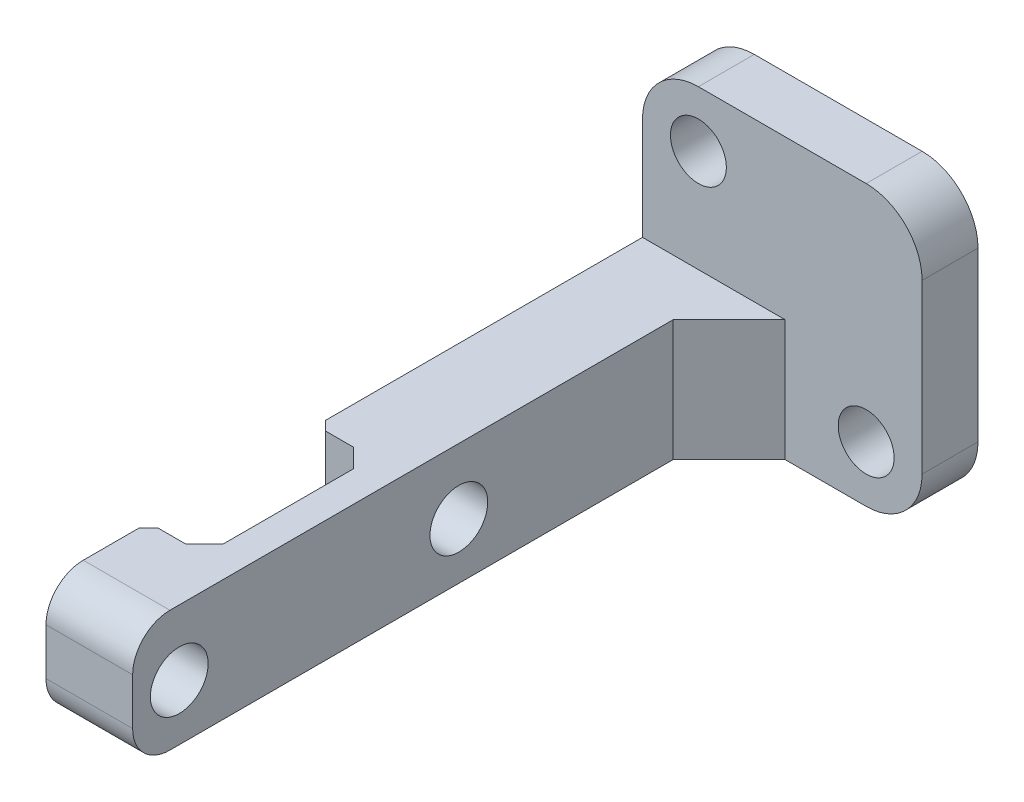
SolidWorks part; units mm, degrees
ref_plane "Front Plane" through (0, 0, 0) normal (0, 0, 1) x (1, 0, 0)
ref_plane "Top Plane" through (0, 0, 0) normal (0, 1, 0) x (1, 0, 0)
ref_plane "Right Plane" through (0, 0, 0) normal (1, 0, 0) x (0, 0, -1)
sketch "Sketch1" plane through (0, 0, 0) normal (0, 1, 0) x (1, 0, 0)
  line L1 (0, 0) -> (28, 0)
  line L2 (0, 0) -> (0, 5)
  line L3 (0, 5) -> (28, 5)
  line L4 (28, 0) -> (28, 5)
  dimension "D1" = 5
  dimension "D2" = 28
extrude "Boss-Extrude1" add sketch "Sketch1" along normal blind 20
chamfer "Chamfer1" distance 15 angle 45 1 edges at (28, 0, -2.5)
sketch "Sketch2" plane through (0, 0, 0) normal (0, 0, 1) x (1, 0, 0)
  line L0 (5, 18) -> (5, 2) construction
  line L1 (5, 18) -> (5, 2)
  line L2 (0, 0) -> (13, 0) construction
  line L3 (5, 6.5) -> (9.6488, 6.5)
  line L4 (5, 6.5) -> (5, 0)
  line L5 (5, 0) -> (9.6488, 0)
  line L6 (9.6488, 6.5) -> (9.6488, 0)
  line M5 (0, 0) -> (13, 0)
  dimension "D1" = 6.5
extrude "Boss-Extrude2" add sketch "Sketch2" along normal blind 28 contours L6 L3 L1 L4 M5
sketch "Sketch3" plane through (0, 0, 0) normal (0, -1, 0) x (1, 0, 0)
  line L0 (5, 28) -> (5, 0) construction
  line L1 (5, 22.5) -> (8, 22.5)
  line L2 (5, 22.5) -> (5, 13.5)
  line L3 (5, 13.5) -> (8, 13.5)
  line L4 (8, 22.5) -> (8, 13.5)
  dimension "D1" = 3
  dimension "D2" = 1
  dimension "D3" = 1
extrude "Cut-Extrude1" cut sketch "Sketch3" against normal blind 12.8
chamfer "Chamfer2" distance 1 angle 45 2 edges at (8, 3.25, 13.5) (8, 3.25, 22.5)
fillet "Fillet1" radius 2 2 edges at (7.3244, 6.5, 28) (7.3244, 0, 28)
chamfer "Chamfer3" distance 0.5 angle 45 2 edges at (5, 3.25, 22.5) (5, 3.25, 13.5)
sketch "Sketch4" plane through (5, 0, 0) normal (-1, 0, 0) x (0, 0, 1)
  arc A0 (25.5, 1.45) -> (25.5, 4.55) centre (25.5, 3) ccw construction
  arc A1 (25.5, 4.55) -> (25.5, 1.45) centre (25.5, 3) ccw construction
  arc A2 (10.5, 4.55) -> (10.5, 1.45) centre (10.5, 3) ccw construction
  arc A3 (10.5, 1.45) -> (10.5, 4.55) centre (10.5, 3) ccw construction
  arc A4 (25.5, 1.45) -> (25.5, 4.55) centre (25.5, 3) ccw
  arc A5 (25.5, 4.55) -> (25.5, 1.45) centre (25.5, 3) ccw
  arc A6 (10.5, 4.55) -> (10.5, 1.45) centre (10.5, 3) ccw
  arc A7 (10.5, 1.45) -> (10.5, 4.55) centre (10.5, 3) ccw
extrude "Cut-Extrude2" cut sketch "Sketch4" against normal blind 12.8
chamfer "Chamfer4" distance 3 angle 45 2 edges at (5, 3.25, 0) (9.6488, 3.25, 0)
chamfer "Chamfer5" distance 3 angle 45 1 edges at (7.3244, 6.5, 0)
sketch "Sketch8" plane through (0, 20, 0) normal (0, 1, 0) x (1, 0, 0)
  line L0 (22.254, 1.284) -> (22.254, 1.158) construction
  line L1 (22.254, 0.746) -> (22.254, 1.158) construction
  line L2 (22.254, 3.714) -> (22.254, 1.284) construction
  line L3 (22.254, 3.714) -> (25.164, 3.714) construction
  line L4 (25.164, 3.714) -> (25.164, 0.75) construction
  line L5 (25.164, 0.746) -> (24.43, 0.746) construction
  line L6 (24.43, 0.746) -> (22.254, 0.746) construction
  line L7 (4.214, 2.802) -> (4.214, 2.092) construction
  line L8 (4.214, 2.092) -> (4.214, 0.772) construction
  line L9 (4.858, 0.772) -> (4.214, 0.772) construction
  line L10 (6.602, 0.772) -> (7.122, 0.772) construction
  line L11 (4.858, 0.772) -> (6.602, 0.772) construction
  line L12 (7.122, 0.772) -> (7.122, 3.484) construction
  line L13 (7.122, 3.682) -> (7.122, 3.484) construction
  line L14 (4.214, 3.682) -> (4.214, 2.802) construction
  line L15 (6.328, 3.682) -> (4.214, 3.682) construction
  line L16 (7.122, 3.682) -> (6.328, 3.682) construction
  line L17 (22.254, 1.284) -> (22.254, 1.158)
  line L18 (22.254, 0.746) -> (22.254, 1.158)
  line L19 (22.254, 3.714) -> (22.254, 1.284)
  line L20 (22.254, 3.714) -> (25.164, 3.714)
  line L21 (25.164, 3.714) -> (25.164, 0.75)
  line L22 (25.164, 0.746) -> (24.43, 0.746)
  line L23 (24.43, 0.746) -> (22.254, 0.746)
  line L24 (4.214, 2.802) -> (4.214, 2.092)
  line L25 (4.214, 2.092) -> (4.214, 0.772)
  line L26 (4.858, 0.772) -> (4.214, 0.772)
  line L27 (6.602, 0.772) -> (7.122, 0.772)
  line L28 (4.858, 0.772) -> (6.602, 0.772)
  line L29 (7.122, 0.772) -> (7.122, 3.484)
  line L30 (7.122, 3.682) -> (7.122, 3.484)
  line L31 (4.214, 3.682) -> (4.214, 2.802)
  line L32 (6.328, 3.682) -> (4.214, 3.682)
  line L33 (7.122, 3.682) -> (6.328, 3.682)
  line L34 (25.252, 3.714) -> (22.254, 3.714) construction
  line L35 (25.164, 0.746) -> (22.254, 0.746)
  line L36 (25.164, 0.746) -> (25.164, 3.714)
  line L37 (25.164, 3.714) -> (22.254, 3.714)
  line L38 (22.254, 0.746) -> (22.254, 3.714)
  line L39 (25.314, 0.596) -> (22.104, 0.596)
  line L40 (25.314, 0.596) -> (25.314, 3.864)
  line L41 (25.314, 3.864) -> (22.104, 3.864)
  line L42 (22.104, 0.596) -> (22.104, 3.864)
  line L44 (4.064, 0.622) -> (7.272, 0.622)
  line L45 (4.064, 0.622) -> (4.064, 3.832)
  line L46 (4.064, 3.832) -> (7.272, 3.832)
  line L47 (7.272, 0.622) -> (7.272, 3.832)
  dimension "D1" = 0.15
  dimension "D2" = 0.15
  dimension "D3" = 0.15
  dimension "D4" = 0.15
  dimension "D5" = 0.15
  dimension "D6" = 0.15
  dimension "D7" = 0.15
  dimension "D8" = 0.15
extrude "Cut-Extrude3" cut sketch "Sketch8" against normal blind 5.4 contours L44 L47 L46 L45 L33 L30 L29 L27 L28 L26 L25 L24 L31 L32 | L30 L33 L32 L31 L24 L25 L26 L28 L27 L29 | L22 L36 L21 L20 L19 L17 L18 L23 | L42 L39 L40 L41 L36 L22 L23 L18 L17 L19 L20 L21
sketch "Sketch9" plane through (0, 0, -5) normal (0, 0, -1) x (-1, 0, 0)
  line L1 (63.3331, 29.3819) -> (-72.7305, 29.3819)
  line L2 (63.3331, 29.3819) -> (63.3331, -4.7966)
  line L3 (63.3331, -4.7966) -> (-72.7305, -4.7966)
  line L4 (-72.7305, 29.3819) -> (-72.7305, -4.7966)
extrude "Cut-Extrude4" cut sketch "Sketch9" against normal up to vertex (8 mm away)
sketch "Sketch10" plane through (0, 0, 3) normal (0, 0, -1) x (-1, 0, 0)
  line L4 (-9.6488, 0) -> (-5, 0)
  line L5 (-5, 0) -> (-5, 6.5)
  line L6 (-5, 6.5) -> (-9.6488, 6.5)
  line L7 (-9.6488, 6.5) -> (-9.6488, 0)
  line L8 (-9.6488, 0) -> (-5, 0)
  line L9 (-5, 0) -> (-5, 6.5)
  line L10 (-5, 6.5) -> (-9.6488, 6.5)
  line L11 (-9.6488, 6.5) -> (-9.6488, 0)
  dimension "D1" = 0
extrude "Boss-Extrude3" add sketch "Sketch10" along normal blind 10
sketch "Sketch12" plane through (0, 0, -7) normal (0, 0, -1) x (-1, 0, 0)
  line L1 (-5, 0) -> (-20, 0)
  line L2 (-5, 0) -> (-5, 15)
  line L3 (-5, 15) -> (-20, 15)
  line L4 (-20, 0) -> (-20, 15)
  dimension "D1" = 15
  dimension "D2" = 15
extrude "Boss-Extrude4" add sketch "Sketch12" against normal blind 3
sketch "Sketch13" plane through (0, 0, -4) normal (0, 0, 1) x (1, 0, 0)
  line L0 (20, 15) -> (20, 0) construction
  line L1 (20, 0) -> (9.6488, 0) construction
  line L2 (5, 6.5) -> (5, 15) construction
  line L3 (5, 15) -> (20, 15) construction
  circle A0 centre (17, 3) radius 1.5
  circle A2 centre (8, 12) radius 1.5
  dimension "D1" = 3
  dimension "D2" = 3
  dimension "D3" = 3
  dimension "D4" = 3
  dimension "D5" = 3
  dimension "D6" = 3
extrude "Cut-Extrude5" cut sketch "Sketch13" against normal blind 5
fillet "Fillet2" radius 3 3 edges at (5, 15, -5.5) (20, 15, -5.5) (20, 0, -5.5)
chamfer "Chamfer6" distance 3 angle 45 1 edges at (9.6488, 3.25, -4)
